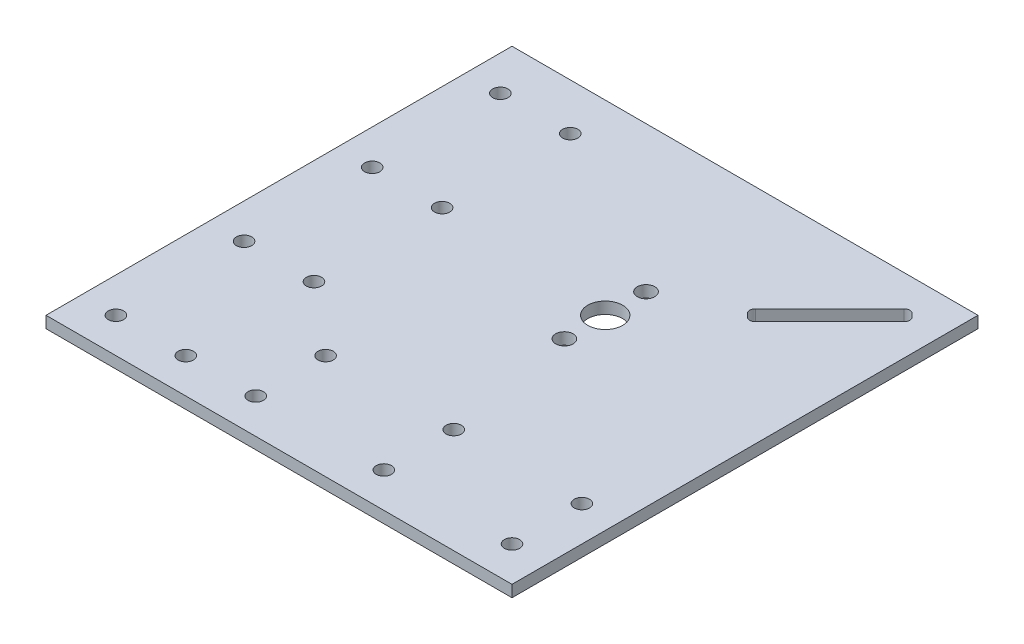
SolidWorks part; units mm, degrees
material "6061-T6 (SS)"
ref_plane "Front" through (0, 0, 0) normal (0, 0, 1) x (1, 0, 0)
ref_plane "Top" through (0, 0, 0) normal (0, 1, 0) x (1, 0, 0)
ref_plane "Right" through (0, 0, 0) normal (1, 0, 0) x (0, 0, -1)
sketch "Sketch1" plane through (0, 0, 0) normal (0, 1, 0) x (1, 0, 0)
  line L1 (0, 0) -> (254, 0)
  line L2 (0, 0) -> (0, 254)
  line L3 (0, 254) -> (254, 254)
  line L4 (254, 0) -> (254, 254)
  dimension "D1" = 254
  dimension "D2" = 254
extrude "Boss-Extrude1" add sketch "Sketch1" along normal blind 6.35
hole_wizard "3/4 (0.75) Diameter Hole1" positions "Sketch2" profile "Sketch3" hole size "3/4" standard "ANSI Inch" end condition up to next
sketch "Sketch2" plane through (0, 6.35, 0) normal (0, 1, 0) x (1, 0, 0)
  line L0 (0, 0) -> (254, 0) construction
  line L1 (0, 254) -> (0, 0) construction
  point P0 (152.4, 152.4)
  dimension "D1" = 152.4
  dimension "D2" = 152.4
sketch "Sketch3" plane through (152.4, 6.35, -152.4) normal (1, 0, 0) x (0, 0, 1)
  line L0 (0, 0) -> (0, 6.35)
  line L1 (0, 6.35) -> (9.525, 6.35)
  line L2 (9.525, 6.35) -> (9.525, 0)
  line L5 (9.525, 0) -> (0, 0)
  line L11 (0, -6.35) -> (0, 107.95) construction
  dimension "Thru Hole Dia." = 19.05
  dimension "Thru Hole Depth" = 6.35
hole_wizard "3/8 (0.375) Diameter Hole1" positions "Sketch4" profile "Sketch5" hole size "3/8" standard "ANSI Inch" end condition up to next
sketch "Sketch4" plane through (0, 6.35, 0) normal (0, 1, 0) x (1, 0, 0)
  circle A1 centre (152.4, 152.4) radius 9.525 construction
  point P0 (152.4, 174.6504)
  point P2 (152.4, 130.1496)
  dimension "D1" = 0
  dimension "D2" = 0
  dimension "D3" = 22.2504
  dimension "D4" = 22.2504
sketch "Sketch5" plane through (152.4, 6.35, -174.6504) normal (1, 0, 0) x (0, 0, 1)
  line L0 (0, 0) -> (0, 6.35)
  line L1 (0, 6.35) -> (4.7625, 6.35)
  line L2 (4.7625, 6.35) -> (4.7625, 0)
  line L5 (4.7625, 0) -> (0, 0)
  line L11 (0, -6.35) -> (0, 107.95) construction
  dimension "Thru Hole Dia." = 9.525
  dimension "Thru Hole Depth" = 6.35
hole_wizard "21/64 (0.32813) Diameter Hole1" positions "Sketch6" profile "Sketch7" hole size "21/64" standard "ANSI Inch" end condition through all
sketch "Sketch6" plane through (0, 6.35, 0) normal (0, 1, 0) x (1, 0, 0)
  line L0 (0, 254) -> (0, 0) construction
  line L1 (0, 0) -> (254, 0) construction
  point P0 (19.05, 19.05)
  dimension "D1" = 19.05
  dimension "D2" = 19.05
sketch "Sketch7" plane through (19.05, 6.35, -19.05) normal (1, 0, 0) x (0, 0, 1)
  line L0 (0, 0) -> (0, 6.35)
  line L1 (0, 6.35) -> (4.1673, 6.35)
  line L2 (4.1673, 6.35) -> (4.1673, 0)
  line L5 (4.1673, 0) -> (0, 0)
  line L11 (0, -6.35) -> (0, 107.95) construction
  dimension "Thru Hole Dia." = 8.3345
  dimension "Thru Hole Depth" = 6.35
pattern_linear "LPattern1" count 2 spacing 38.1 along (1, 0, 0) count 4 spacing 69.85 along (0, 0, -1) of "21/64 (0.32813) Diameter Hole1"
hole_wizard "21/64 (0.32813) Diameter Hole2" positions "Sketch8" profile "Sketch9" hole size "21/64" standard "ANSI Inch" end condition through all
sketch "Sketch8" plane through (0, 6.35, 0) normal (0, 1, 0) x (1, 0, 0)
  line L0 (254, 0) -> (254, 254) construction
  line L1 (0, 0) -> (254, 0) construction
  point P0 (234.95, 19.05)
  dimension "D1" = 19.05
  dimension "D2" = 19.05
sketch "Sketch9" plane through (234.95, 6.35, -19.05) normal (1, 0, 0) x (0, 0, 1)
  line L0 (0, 0) -> (0, 6.35)
  line L1 (0, 6.35) -> (4.1673, 6.35)
  line L2 (4.1673, 6.35) -> (4.1673, 0)
  line L5 (4.1673, 0) -> (0, 0)
  line L11 (0, -6.35) -> (0, 107.95) construction
  dimension "Thru Hole Dia." = 8.3345
  dimension "Thru Hole Depth" = 6.35
pattern_linear "LPattern2" count 2 spacing 38.1 along (0, 0, -1) count 3 spacing 69.85 along (-1, 0, 0) of "21/64 (0.32813) Diameter Hole2"
sketch "Sketch10" plane through (0, 6.35, 0) normal (0, 1, 0) x (1, 0, 0)
  line L0 (188.0849, 194.1915) -> (232.9862, 239.0928)
  line L1 (232.9862, 239.0928) -> (239.0928, 232.9862)
  line L2 (239.0928, 232.9862) -> (194.1915, 188.0849)
  line L3 (194.1915, 188.0849) -> (188.0849, 194.1915)
  line L4 (254, 254) -> (0, 254) construction
  line L5 (254, 254) -> (135.4189, 135.4189) construction
  dimension "D1" = 63.5
  dimension "D2" = 8.636
  dimension "D3" = 4.318
  dimension "D4" = 45
  dimension "D6" = 25.4
extrude "Cut-Extrude1" cut sketch "Sketch10" against normal through all
fillet "Fillet1" radius 3.175 4 edges at (188.0849, 3.175, -194.1915) (194.1915, 3.175, -188.0849) (239.0928, 3.175, -232.9862) (232.9862, 3.175, -239.0928)
